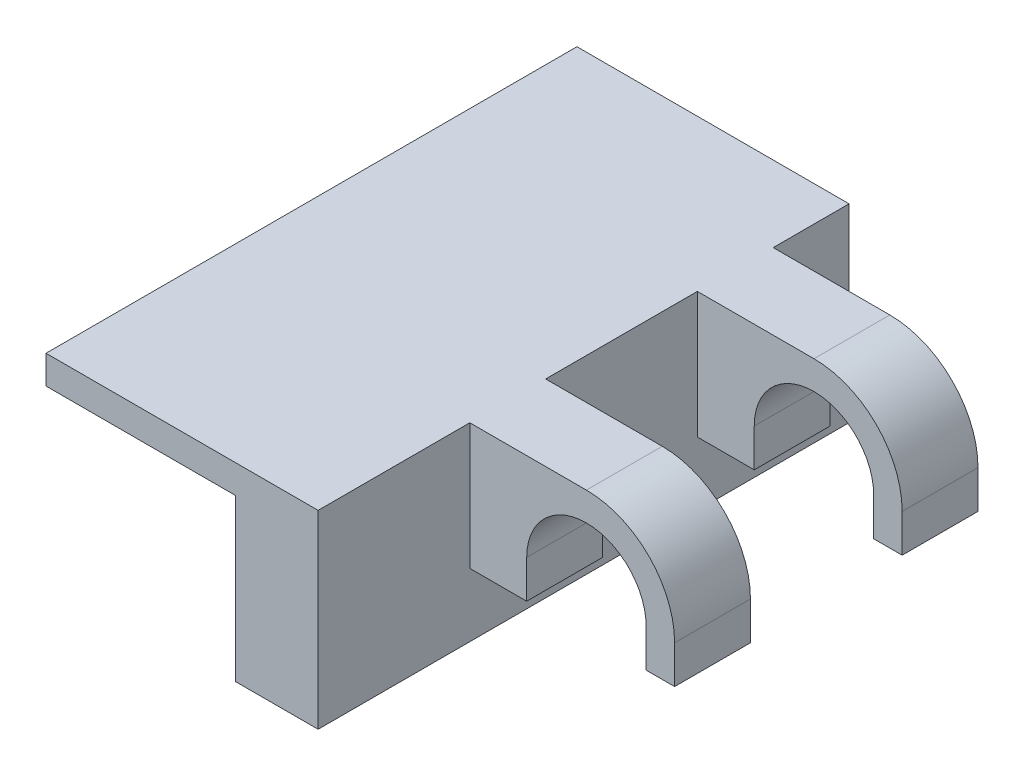
SolidWorks part; units mm, degrees
ref_plane "Ebene vorne" through (0, 0, 0) normal (0, 0, 1) x (1, 0, 0)
ref_plane "Ebene oben" through (0, 0, 0) normal (0, 1, 0) x (1, 0, 0)
ref_plane "Ebene rechts" through (0, 0, 0) normal (1, 0, 0) x (0, 0, -1)
sketch "Skizze1" plane through (0, 0, 0) normal (0, 0, 1) x (1, 0, 0)
  line L0 (-195, 0) -> (195, 0) construction
  line L1 (-198.15, 0) -> (-198.15, -2)
  line L2 (-191.85, 0) -> (-191.85, -2)
  line L3 (-188.85, -5.35) -> (188.85, -5.35)
  line L4 (-198.15, -2) -> (-199.65, -2)
  line L5 (-199.65, -2) -> (-199.65, 0)
  line L6 (-195, 4.65) -> (195, 4.65)
  line L7 (0, 4.65) -> (0, -5.35) construction
  line L8 (-191.85, -2) -> (-188.85, -2)
  line L9 (-188.85, -2) -> (-188.85, -5.35)
  line L10 (188.85, -2) -> (188.85, -5.35)
  line L11 (191.85, -2) -> (188.85, -2)
  line L12 (199.65, -2) -> (199.65, 0)
  line L13 (198.15, -2) -> (199.65, -2)
  line L14 (191.85, 0) -> (191.85, -2)
  line L15 (198.15, 0) -> (198.15, -2)
  arc A0 (-198.15, 0) -> (-191.85, 0) centre (-195, 0) cw
  arc A1 (-199.65, 0) -> (-195, 4.65) centre (-195, 0) cw
  arc A2 (199.65, 0) -> (195, 4.65) centre (195, 0) ccw
  arc A3 (198.15, 0) -> (191.85, 0) centre (195, 0) ccw
  point P3 (0, 0)
  dimension "D2" = 3.15
  dimension "D1" = 390
  dimension "D3" = 1.5
  dimension "D4" = 2
  dimension "D5" = 10
  dimension "D6" = 3
extrude "Aufsatz-Linear austragen2" add sketch "Skizze1" along normal mid plane 28
sketch "Skizze3" plane through (0, -5.35, 0) normal (0, -1, 0) x (1, 0, 0)
  line L0 (-188.85, 14) -> (-188.85, -14) construction
  line L1 (-199.65, 14) -> (-188.85, 14)
  line L2 (-199.65, 14) -> (-199.65, 10)
  line L3 (-199.65, 10) -> (-188.85, 10)
  line L4 (-188.85, 14) -> (-188.85, 10)
  line L5 (-199.65, 14) -> (-199.65, -14) construction
  line L6 (-199.65, 6) -> (-188.85, 6)
  line L7 (-199.65, 6) -> (-199.65, -2)
  line L8 (-199.65, -2) -> (-188.85, -2)
  line L9 (-188.85, 6) -> (-188.85, -2)
  line L10 (-188.85, 14) -> (-188.85, -14) construction
  line L11 (199.65, 14) -> (199.65, -14) construction
  line L12 (-199.65, -14) -> (-188.85, -14)
  line L13 (-199.65, -14) -> (-199.65, -6)
  line L14 (-199.65, -6) -> (-188.85, -6)
  line L15 (-188.85, -14) -> (-188.85, -6)
  line L16 (188.85, 14) -> (199.65, 14)
  line L17 (188.85, 14) -> (188.85, 6)
  line L18 (188.85, 6) -> (199.65, 6)
  line L19 (199.65, 14) -> (199.65, 6)
  line L20 (188.85, 14) -> (188.85, -14) construction
  line L21 (188.85, 2) -> (199.65, 2)
  line L22 (188.85, 2) -> (188.85, -6)
  line L23 (188.85, -6) -> (199.65, -6)
  line L24 (199.65, 2) -> (199.65, -6)
  line L26 (188.85, -10) -> (199.65, -10)
  line L27 (188.85, -10) -> (188.85, -14)
  line L28 (188.85, -14) -> (199.65, -14)
  line L29 (199.65, -10) -> (199.65, -14)
  dimension "D1" = 4
  dimension "D2" = 4
  dimension "D3" = 4
  dimension "D4" = 8
  dimension "D5" = 4
  dimension "D6" = 4
extrude "Schnitt-Linear austragen1" cut sketch "Skizze3" against normal through all
sketch "Skizze4" plane through (0, 0, 14) normal (0, 0, 1) x (1, 0, 0)
  line L0 (174.5, 4.65) -> (174.5, 3.15)
  line L1 (188.85, 4.65) -> (-188.85, 4.65) construction
  line L2 (174.5, 3.15) -> (184.5, 3.15)
  line L3 (184.5, 3.15) -> (184.5, -5.35)
  line L4 (-188.85, -5.35) -> (188.85, -5.35) construction
  line L5 (184.5, -5.35) -> (-199.65, -5.35)
  line L6 (-199.65, -5.35) -> (-199.65, 4.65)
  line L7 (-199.65, 4.65) -> (174.5, 4.65)
  line L8 (-199.65, 0) -> (-199.65, -2) construction
  line L10 (0, 4.65) -> (0, -5.35) construction
  dimension "D1" = 369
  dimension "D2" = 1.5
  dimension "D3" = 10
extrude "Schnitt-Linear austragen2" cut sketch "Skizze4" against normal through all
